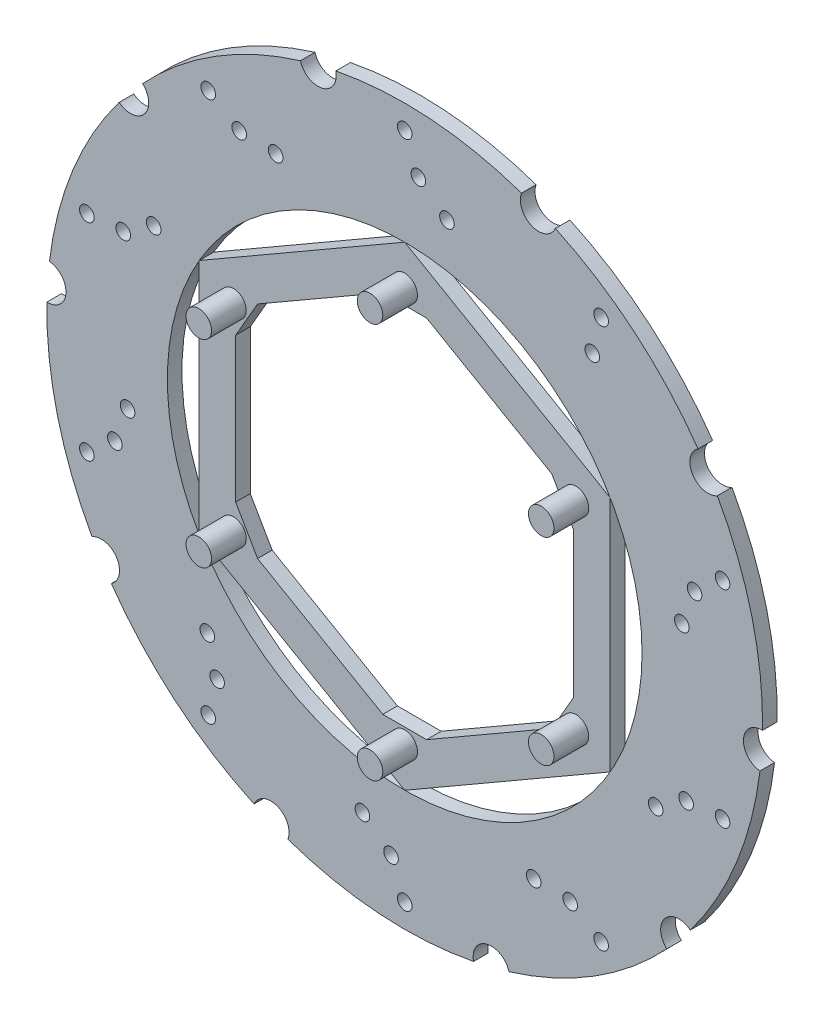
SolidWorks part; units mm, degrees
ref_plane "Front Plane" through (0, 0, 0) normal (0, 0, 1) x (1, 0, 0)
ref_plane "Top Plane" through (0, 0, 0) normal (0, 1, 0) x (1, 0, 0)
ref_plane "Right Plane" through (0, 0, 0) normal (1, 0, 0) x (0, 0, -1)
sketch "Sketch1" plane through (0, 0, 0) normal (0, 0, 1) x (1, 0, 0)
  line L0 (0, 65) -> (0, 53.453) construction
  line L2 (0, 65) -> (-56.2917, 32.5) construction
  line L3 (-56.2917, 32.5) -> (-56.2917, -32.5) construction
  line L4 (-56.2917, -32.5) -> (0, -65) construction
  line L5 (0, -65) -> (56.2917, -32.5) construction
  line L6 (56.2917, -32.5) -> (56.2917, 32.5) construction
  line L7 (56.2917, 32.5) -> (0, 65) construction
  line L13 (40.2917, 30.1906) -> (6, 49.9889) construction
  line L14 (-6, 49.9889) -> (-40.2917, 30.1906) construction
  line L15 (-46.2917, 19.7983) -> (-46.2917, -19.7983) construction
  line L16 (-40.2917, -30.1906) -> (-6, -49.9889) construction
  line L17 (6, -49.9889) -> (40.2917, -30.1906) construction
  line L18 (46.2917, -19.7983) -> (46.2917, 19.7983) construction
  line L19 (40.2917, 30.1906) -> (46.2917, 19.7983) construction
  line L20 (46.2917, -19.7983) -> (40.2917, -30.1906) construction
  line L21 (6, -49.9889) -> (-6, -49.9889) construction
  line L22 (-40.2917, -30.1906) -> (-46.2917, -19.7983) construction
  line L23 (-46.2917, 19.7983) -> (-40.2917, 30.1906) construction
  line L24 (-6, 49.9889) -> (6, 49.9889) construction
  line L25 (46.2917, 26.7265) -> (0, 53.453) construction
  line L26 (46.2917, -26.7265) -> (46.2917, 26.7265) construction
  line L27 (0, -53.453) -> (46.2917, -26.7265) construction
  line L28 (0, -53.453) -> (0, -65) construction
  line L29 (-46.2917, -26.7265) -> (0, -53.453) construction
  line L30 (-46.2917, 26.7265) -> (-46.2917, -26.7265) construction
  line L31 (0, 53.453) -> (-46.2917, 26.7265) construction
  line L32 (0, 49.9889) -> (0, -49.9889) construction
  circle A0 centre (0, 0) radius 98
  circle A1 centre (0, 0) radius 65
  point P32 (0, 0)
  dimension "D1" = 196
  dimension "D4" = 6
  dimension "D3" = 10
  dimension "D5" = 30
  dimension "D6" = 12
  dimension "D7" = 65
  dimension "D8" = 56.2917
  dimension "D2" = 33
extrude "Boss-Extrude1" add sketch "Sketch1" along normal blind 4
sketch "Sketch2" plane through (0, 0, 4) normal (0, 0, 1) x (1, 0, 0)
  line L0 (0, 0) -> (0, 134.7318) construction
  line L1 (-31.5585, 0) -> (31.5585, 0) construction
  circle A0 centre (0, 91.5266) radius 2
  circle A1 centre (3.7396, 82.2522) radius 2
  circle A2 centre (11.5746, 76.0382) radius 2
  circle A3 centre (53.798, 74.0466) radius 2
  circle A4 centre (51.372, 64.3453) radius 2
  circle A5 centre (54.0582, 54.7128) radius 2
  circle A6 centre (87.047, 28.2833) radius 2
  circle A7 centre (79.3821, 21.8607) radius 2
  circle A8 centre (75.8934, 12.489) radius 2
  circle A9 centre (87.047, -28.2833) radius 2
  circle A10 centre (77.0709, -28.9739) radius 2
  circle A11 centre (68.7399, -34.5052) radius 2
  circle A12 centre (53.798, -74.0466) radius 2
  circle A13 centre (45.3212, -68.7415) radius 2
  circle A14 centre (35.3301, -68.3196) radius 2
  circle A15 centre (0, -91.5266) radius 2
  circle A16 centre (-3.7396, -82.2522) radius 2
  circle A17 centre (-11.5746, -76.0382) radius 2
  circle A18 centre (-53.798, -74.0466) radius 2
  circle A19 centre (-51.372, -64.3453) radius 2
  circle A20 centre (-54.0582, -54.7128) radius 2
  circle A21 centre (-87.047, -28.2833) radius 2
  circle A22 centre (-79.3821, -21.8607) radius 2
  circle A23 centre (-75.8934, -12.489) radius 2
  circle A24 centre (-87.047, 28.2833) radius 2
  circle A25 centre (-77.0709, 28.9739) radius 2
  circle A26 centre (-68.7399, 34.5052) radius 2
  circle A27 centre (-53.798, 74.0466) radius 2
  circle A28 centre (-45.3212, 68.7415) radius 2
  circle A29 centre (-35.3301, 68.3196) radius 2
  spline S0 degree 2 poles (0, 91.5266) (1.6919, 80.7219) (11.5746, 76.0382) knots 0 0 0 1 1 1
  point P13 (0, 0)
  point P69 (0, 0)
  dimension "D3" = 4
  dimension "D4" = 4
  dimension "D5" = 4
  dimension "D1" = 10
  dimension "D2" = 10
  dimension "D6" = 10
extrude "Cut-Extrude1" cut sketch "Sketch2" against normal blind 14
sketch "Sketch3" plane through (0, 0, 4) normal (0, 0, 1) x (1, 0, 0)
  line L0 (32.1488, 92.9983) -> (41.385, 89.1944)
  line L1 (80.672, 56.3406) -> (85.9083, 47.8343)
  line L2 (98.3812, -1.8373) -> (97.6176, -11.7969)
  line L3 (78.5121, -59.3134) -> (72.0402, -66.9221)
  line L4 (28.6541, -94.1338) -> (18.946, -96.4853)
  line L5 (-32.1488, -92.9983) -> (-41.385, -89.1944)
  line L6 (-80.672, -56.3406) -> (-85.9083, -47.8343)
  line L7 (-98.3812, 1.8373) -> (-97.6176, 11.7969)
  line L8 (-78.5121, 59.3134) -> (-72.0402, 66.9221)
  line L9 (-28.6541, 94.1338) -> (-18.946, 96.4853)
  arc A0 (32.1488, 92.9983) -> (41.385, 89.1944) centre (36.677, 90.8779) ccw
  circle A1 centre (0, 0) radius 98 construction
  arc A2 (80.672, 56.3406) -> (85.9083, 47.8343) centre (83.089, 51.9636) ccw
  arc A3 (98.3812, -1.8373) -> (97.6176, -11.7969) centre (97.7639, -6.799) ccw
  arc A4 (78.5121, -59.3134) -> (72.0402, -66.9221) centre (75.0963, -62.9647) ccw
  arc A5 (28.6541, -94.1338) -> (18.946, -96.4853) centre (23.7444, -95.08) ccw
  arc A6 (-32.1488, -92.9983) -> (-41.385, -89.1944) centre (-36.677, -90.8779) ccw
  arc A7 (-80.672, -56.3406) -> (-85.9083, -47.8343) centre (-83.089, -51.9636) ccw
  arc A8 (-98.3812, 1.8373) -> (-97.6176, 11.7969) centre (-97.7639, 6.799) ccw
  arc A9 (-78.5121, 59.3134) -> (-72.0402, 66.9221) centre (-75.0963, 62.9647) ccw
  arc A10 (-28.6541, 94.1338) -> (-18.946, 96.4853) centre (-23.7444, 95.08) ccw
  point P35 (0, 0)
  dimension "D1" = 5
  dimension "D2" = 10
extrude "Cut-Extrude2" cut sketch "Sketch3" against normal up to vertex (4 mm away) up to point (0, 0, 0)
ref_plane "Plane1" through (0, 0, 0) normal (0, 0, 1) x (1, 0, 0)
sketch "Sketch6" plane through (0, 0, 0) normal (0, 0, 1) x (1, 0, 0)
  line L0 (40.2917, 30.1906) -> (46.2917, 19.7983) construction
  line L1 (46.2917, -19.7983) -> (46.2917, 19.7983) construction
  line L2 (56.2917, -32.5) -> (56.2917, 32.5) construction
  line L3 (46.2917, -19.7983) -> (40.2917, -30.1906) construction
  line L4 (6, -49.9889) -> (40.2917, -30.1906) construction
  line L5 (6, -49.9889) -> (-6, -49.9889) construction
  line L6 (0, -65) -> (56.2917, -32.5) construction
  line L7 (-56.2917, -32.5) -> (0, -65) construction
  line L8 (-40.2917, -30.1906) -> (-46.2917, -19.7983) construction
  line L9 (-40.2917, -30.1906) -> (-6, -49.9889) construction
  line L10 (-46.2917, 19.7983) -> (-40.2917, 30.1906) construction
  line L11 (-46.2917, 19.7983) -> (-46.2917, -19.7983) construction
  line L12 (-56.2917, 32.5) -> (-56.2917, -32.5) construction
  line L13 (0, 65) -> (-56.2917, 32.5) construction
  line L14 (40.2917, 30.1906) -> (6, 49.9889) construction
  line L15 (56.2917, 32.5) -> (0, 65) construction
  line L16 (-6, 49.9889) -> (6, 49.9889) construction
  line L17 (-6, 49.9889) -> (-40.2917, 30.1906) construction
  line L18 (40.2917, 30.1906) -> (46.2917, 19.7983)
  line L19 (46.2917, -19.7983) -> (46.2917, 19.7983)
  line L20 (56.2917, -32.5) -> (56.2917, 32.5)
  line L21 (46.2917, -19.7983) -> (40.2917, -30.1906)
  line L22 (6, -49.9889) -> (40.2917, -30.1906)
  line L23 (6, -49.9889) -> (-6, -49.9889)
  line L24 (0, -65) -> (56.2917, -32.5)
  line L25 (-56.2917, -32.5) -> (0, -65)
  line L26 (-40.2917, -30.1906) -> (-46.2917, -19.7983)
  line L27 (-40.2917, -30.1906) -> (-6, -49.9889)
  line L28 (-46.2917, 19.7983) -> (-40.2917, 30.1906)
  line L29 (-46.2917, 19.7983) -> (-46.2917, -19.7983)
  line L30 (-56.2917, 32.5) -> (-56.2917, -32.5)
  line L31 (0, 65) -> (-56.2917, 32.5)
  line L32 (40.2917, 30.1906) -> (6, 49.9889)
  line L33 (56.2917, 32.5) -> (0, 65)
  line L34 (-6, 49.9889) -> (6, 49.9889)
  line L35 (-6, 49.9889) -> (-40.2917, 30.1906)
extrude "Boss-Extrude3" add sketch "Sketch6" along normal blind 4 separate body
sketch "Sketch7" plane through (0, 0, 4) normal (0, 0, 1) x (1, 0, 0)
  line L0 (-56.2917, 32.5) -> (-43.2917, 24.9944) construction
  line L1 (-46.2917, 19.7983) -> (-40.2917, 30.1906) construction
  circle A0 centre (-46.8885, 27.0711) radius 3.5
  circle A1 centre (0, 54.1422) radius 3.5
  circle A2 centre (46.8885, 27.0711) radius 3.5
  circle A3 centre (46.8885, -27.0711) radius 3.5
  circle A4 centre (0, -54.1422) radius 3.5
  circle A5 centre (-46.8885, -27.0711) radius 3.5
  point P19 (0, 0)
  dimension "D1" = 7
  dimension "D3" = 54.1422
  dimension "D2" = 6
extrude "Boss-Extrude4" add sketch "Sketch7" along normal blind 9.5
